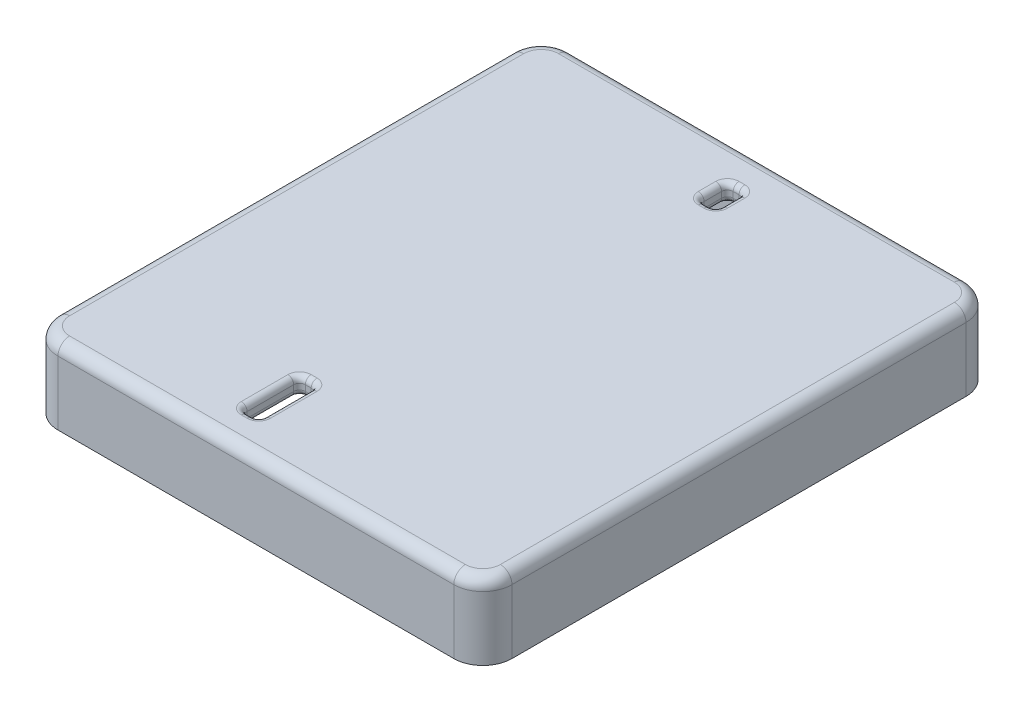
SolidWorks part; units mm, degrees
ref_plane "Front Plane" through (0, 0, 0) normal (0, 0, 1) x (1, 0, 0)
ref_plane "Top Plane" through (0, 0, 0) normal (0, 1, 0) x (1, 0, 0)
ref_plane "Right Plane" through (0, 0, 0) normal (1, 0, 0) x (0, 0, -1)
sketch "Sketch1" plane through (0, 0, 0) normal (0, 1, 0) x (1, 0, 0)
  line L1 (-37.5, 42.5) -> (37.5, 42.5)
  line L2 (-37.5, 42.5) -> (-37.5, -42.5)
  line L3 (-37.5, -42.5) -> (37.5, -42.5)
  line L4 (37.5, 42.5) -> (37.5, -42.5)
  line L5 (-37.5, 42.5) -> (37.5, -42.5) construction
  line L6 (-37.5, -42.5) -> (37.5, 42.5) construction
  point P0 (0, 0)
  dimension "D1" = 75
  dimension "D2" = 85
extrude "Extrude-Thin1" add sketch "Sketch1" along normal blind 10 thin thin type one direction wall 1.5
sketch "Sketch2" plane through (0, 10, 0) normal (0, 1, 0) x (1, 0, 0)
  line L4 (39, -44) -> (39, 44)
  line L5 (39, 44) -> (-39, 44)
  line L6 (-39, 44) -> (-39, -44)
  line L7 (-39, -44) -> (39, -44)
  line L8 (39, -44) -> (39, 44)
  line L9 (39, 44) -> (-39, 44)
  line L10 (-39, 44) -> (-39, -44)
  line L11 (-39, -44) -> (39, -44)
  dimension "D1" = 0
extrude "Boss-Extrude1" add sketch "Sketch2" along normal blind 3
sketch "Sketch3" plane through (37.5, 0, 0) normal (1, 0, 0) x (0, 0, -1)
  line L0 (-44, 10) -> (44, 10) construction
  line L1 (-44, 13) -> (-44, 0) construction
  line L2 (44, 13) -> (44, 0) construction
  line L3 (-44, 13) -> (44, 13) construction
  line L4 (-44, 5) -> (44, 5) construction
  line L5 (0, 10) -> (0, 0) construction
  line L7 (-15, 6) -> (15, 6)
  line L8 (-15, 6) -> (-15, 4)
  line L9 (-15, 4) -> (15, 4)
  line L10 (15, 6) -> (15, 4)
  line L11 (-15, 6) -> (15, 4) construction
  line L12 (-15, 4) -> (15, 6) construction
  point P13 (0, 5)
  dimension "D1" = 3
  dimension "D2" = 5
  dimension "D3" = 30
  dimension "D4" = 2
fillet "Fillet1" radius 5 8 edges at (-37.5, 5, 42.5) (37.5, 5, 42.5) (37.5, 5, -42.5) (-37.5, 5, -42.5) (-39, 6.5, -44) (-39, 6.5, 44) (39, 6.5, 44) (39, 6.5, -44)
fillet "Fillet2" radius 2 8 edges at (37.5355, 13, -42.5355) (39, 13, 0) (37.5355, 13, 42.5355) (0, 13, 44) (-37.5355, 13, 42.5355) (-39, 13, 0) (-37.5355, 13, -42.5355) (0, 13, -44)
extrude "Boss-Extrude2" add sketch "Sketch3" against normal blind 0.5 draft 64 contours L7 L10 L9 L8
mirror "Mirror2" about plane through (0, 0, 0) normal (1, 0, 0) of "Boss-Extrude2"
sketch "Sketch4" plane through (0, 13, 0) normal (0, 1, 0) x (1, 0, 0)
  line L1 (-8.5, -28) -> (-5.5, -28)
  line L2 (-8.5, -28) -> (-8.5, -38)
  line L3 (-8.5, -38) -> (-5.5, -38)
  line L4 (-5.5, -28) -> (-5.5, -38)
  line L5 (-8.5, -28) -> (-5.5, -38) construction
  line L6 (-8.5, -38) -> (-5.5, -28) construction
  line L8 (-34, 44) -> (34, 44) construction
  line L9 (-0.5, 37.5) -> (2.5, 37.5)
  line L10 (-0.5, 37.5) -> (-0.5, 32.5)
  line L11 (-0.5, 32.5) -> (2.5, 32.5)
  line L12 (2.5, 37.5) -> (2.5, 32.5)
  line L13 (-0.5, 37.5) -> (2.5, 32.5) construction
  line L14 (-0.5, 32.5) -> (2.5, 37.5) construction
  line L15 (-39, -39) -> (-39, 39) construction
  line L16 (34, -44) -> (-34, -44) construction
  point P0 (-7, -33)
  point P9 (1, 35)
  dimension "D1" = 32
  dimension "D2" = 11
  dimension "D3" = 3
  dimension "D4" = 10
  dimension "D5" = 40
  dimension "D6" = 9
  dimension "D7" = 3
  dimension "D8" = 5
extrude "Cut-Extrude2" cut sketch "Sketch4" against normal up to next
fillet "Fillet3" radius 1 12 edges at (2.5, 13, -35) (2.5, 10, -35) (2.5, 11.5, -37.5) (-0.5, 11.5, -32.5) (-0.5, 13, -35) (-0.5, 11.5, -37.5) (-0.5, 10, -35) (2.5, 11.5, -32.5) (1, 10, -32.5) (1, 13, -32.5) (1, 13, -37.5) (1, 10, -37.5)
fillet "Fillet4" radius 1 12 edges at (-7, 10, 38) (-7, 13, 38) (-7, 13, 28) (-7, 10, 28) (-5.5, 11.5, 28) (-5.5, 13, 33) (-5.5, 11.5, 38) (-5.5, 10, 33) (-8.5, 11.5, 38) (-8.5, 13, 33) (-8.5, 11.5, 28) (-8.5, 10, 33)
